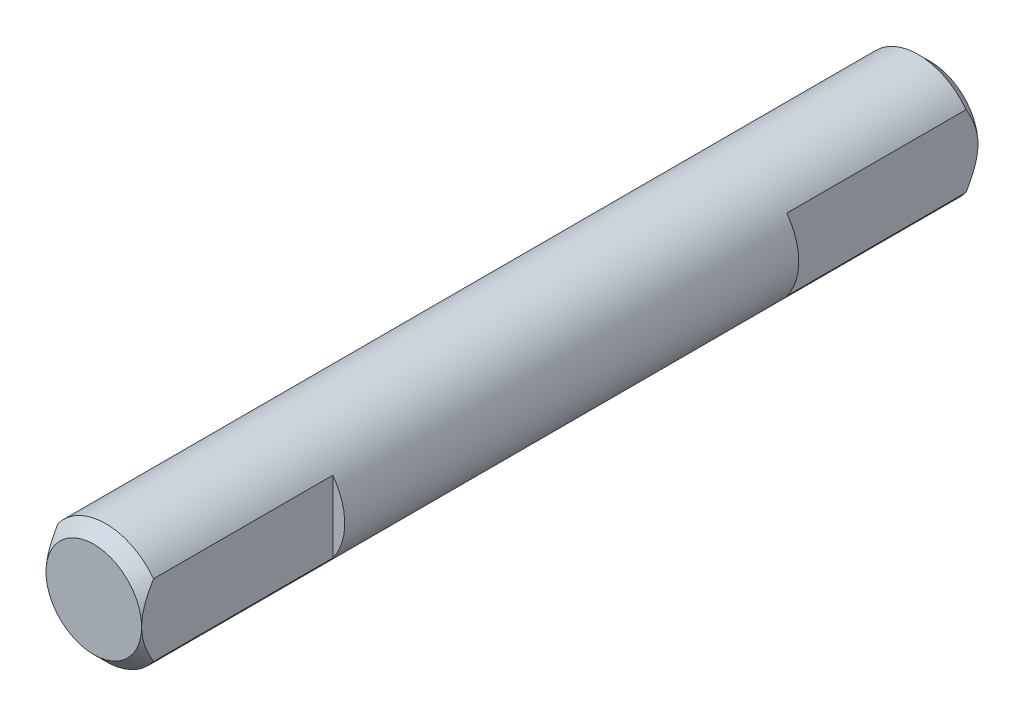
SolidWorks part; units mm, degrees
ref_plane "Front Plane" through (0, 0, 0) normal (0, 0, 1) x (1, 0, 0)
ref_plane "Top Plane" through (0, 0, 0) normal (0, 1, 0) x (1, 0, 0)
ref_plane "Right Plane" through (0, 0, 0) normal (1, 0, 0) x (0, 0, -1)
sketch "Sketch1" plane through (0, 0, 0) normal (0, 0, 1) x (1, 0, 0)
  circle A0 centre (0, 0) radius 2.5
  dimension "D1" = 5
extrude "Boss-Extrude1" add sketch "Sketch1" along normal blind 35
chamfer "Chamfer1" distance 0.5 angle 45 2 edges at (2.5, 0, 0) (2.5, 0, 35)
sketch "Sketch2" plane through (0, 0, 35) normal (0, 0, 1) x (1, 0, 0)
  line L0 (2, 1.5557) -> (2, -1.5557)
  line L1 (0, 0) -> (0, 50000) construction
  line L2 (-2, 1.5557) -> (-2, -1.5557)
  line L3 (-2, 1.5557) -> (-4.9433, 1.4393)
  line L4 (-4.9433, 1.4393) -> (-4.7172, -1.8613)
  line L5 (-4.7172, -1.8613) -> (-3.4716, -2.9471)
  line L6 (-3.4716, -2.9471) -> (-2.969, -3.1272)
  line L7 (-2.969, -3.1272) -> (-2, -1.5557)
  line L8 (2, -1.5557) -> (4.461, -1.6955)
  line L9 (4.461, -1.6955) -> (5.2191, -0.466)
  line L10 (5.2191, -0.466) -> (5.0683, 0.17)
  line L11 (3.4167, 1.6531) -> (3.0346, 1.8887)
  line L12 (3.0346, 1.8887) -> (2, 1.5557)
  line L13 (3.4167, 1.6531) -> (5.0683, 0.17)
  dimension "D1" = 2
extrude "Cut-Extrude1" cut sketch "Sketch2" against normal blind 8
ref_plane "Plane1" through (0, 0, 17.5) normal (0, 0, 1) x (1, 0, 0)
mirror "Mirror1" about plane through (0, 0, 17.5) normal (0, 0, 1) of "Cut-Extrude1"
